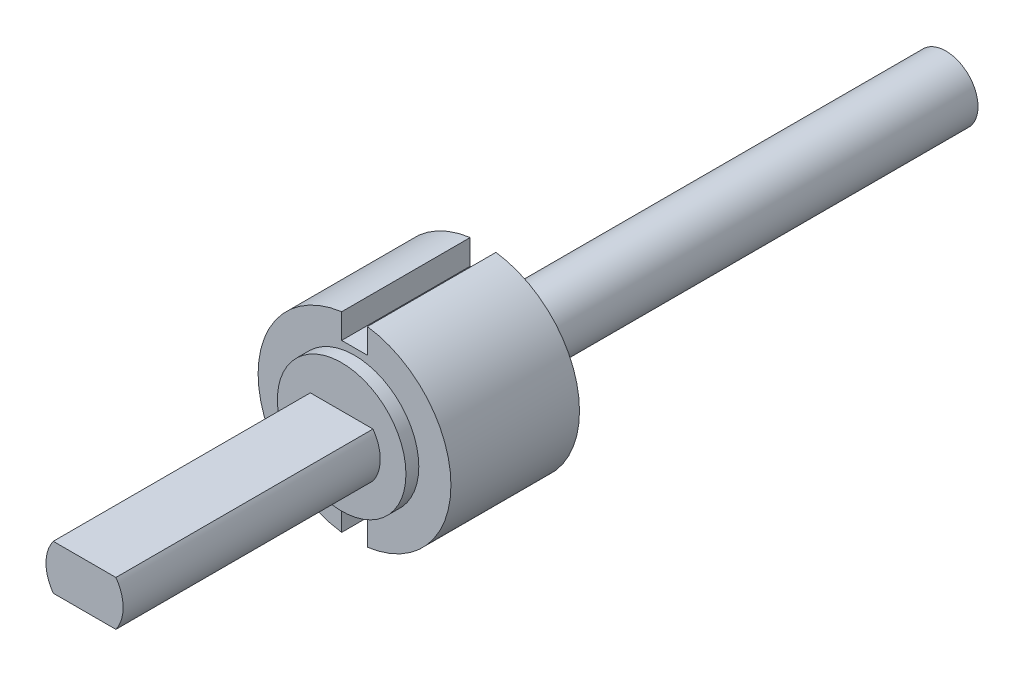
SolidWorks part; units mm, degrees
ref_plane "Front" through (0, 0, 0) normal (0, 0, 1) x (1, 0, 0)
ref_plane "Top" through (0, 0, 0) normal (0, 1, 0) x (1, 0, 0)
ref_plane "Right" through (0, 0, 0) normal (1, 0, 0) x (0, 0, -1)
sketch "Эскиз1" plane through (0, 0, 0) normal (0, 0, 1) x (1, 0, 0)
  circle A2 centre (0, 0) radius 7.5
  dimension "D3" = 15
extrude "Бобышка-Вытянуть1" add sketch "Эскиз1" along normal mid plane 10
sketch "Эскиз6" plane through (0, 0, 5) normal (0, 0, 1) x (1, 0, 0)
  circle A0 centre (0, 0) radius 5
  dimension "D1" = 10
sketch "Эскиз9" plane through (0, 0, -5) normal (0, 0, -1) x (-1, 0, 0)
  circle A0 centre (0, 0) radius 2.5
  dimension "D1" = 5
extrude "Бобышка-Вытянуть6" add sketch "Эскиз6" along normal blind 1
sketch "Эскиз10" plane through (0, 0, 6) normal (0, 0, 1) x (1, 0, 0)
  line L0 (-2.4367, 1.75) -> (2.4367, 1.75)
  line L1 (-2.4367, -1.75) -> (2.4367, -1.75)
  circle A0 centre (0, 0) radius 3
  dimension "D1" = 6
  dimension "D2" = 3.5
extrude "Бобышка-Вытянуть7" add sketch "Эскиз10" along normal blind 20 contours L0 A0 L1
extrude "Бобышка-Вытянуть8" add sketch "Эскиз9" along normal blind 36
sketch "Эскиз11" plane through (0, 0, 5) normal (0, 0, 1) x (1, 0, 0)
  line L0 (0, 7.5) -> (0, -7.5) construction
  line L1 (-7.5, 0) -> (7.5, 0) construction
  line L3 (-1, 7.5) -> (1, 7.5)
  line L4 (-1, 7.5) -> (-1, 5.5)
  line L5 (-1, 5.5) -> (1, 5.5)
  line L6 (1, 7.5) -> (1, 5.5)
  line L7 (1, -7.5) -> (-1, -7.5)
  line L8 (1, -7.5) -> (1, -5.5)
  line L9 (1, -5.5) -> (-1, -5.5)
  line L10 (-1, -7.5) -> (-1, -5.5)
  circle A0 centre (0, 0) radius 7.5 construction
  dimension "D1" = 2
  dimension "D2" = 2
extrude "Вырез-Вытянуть1" cut sketch "Эскиз11" against normal blind 10
